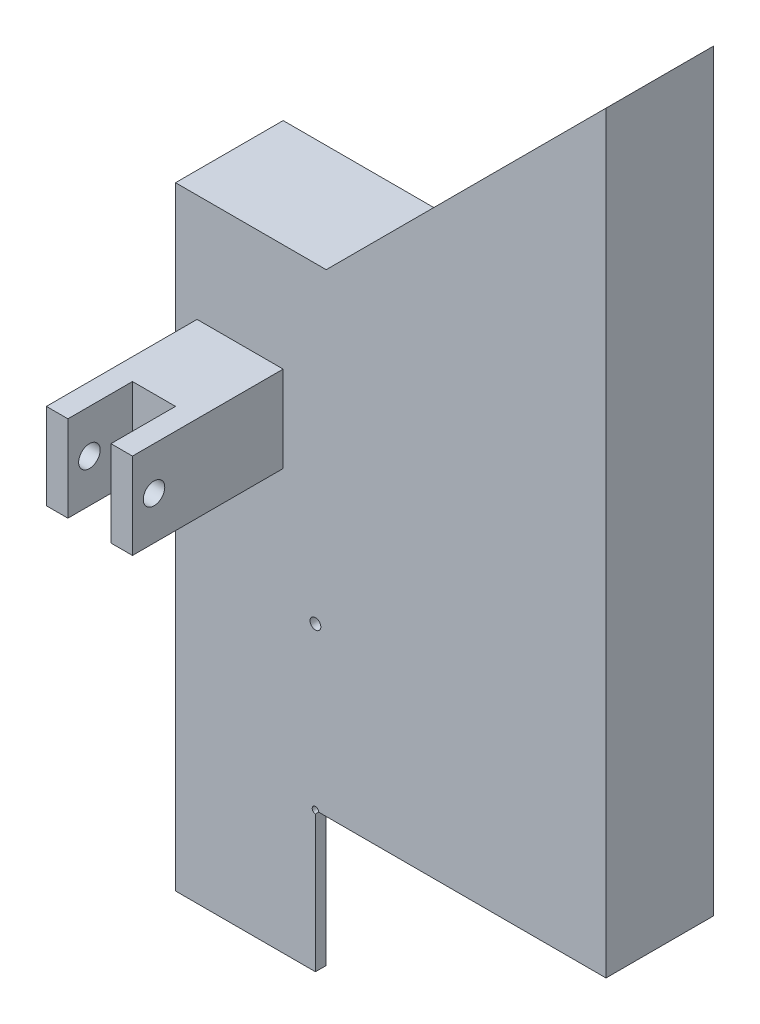
SolidWorks part; units mm, degrees
ref_plane "Přední rovina" through (0, 0, 0) normal (0, 0, 1) x (1, 0, 0)
ref_plane "Horní rovina" through (0, 0, 0) normal (0, 1, 0) x (1, 0, 0)
ref_plane "Pravá rovina" through (0, 0, 0) normal (1, 0, 0) x (0, 0, -1)
sketch "Skica1" plane through (0, 0, 0) normal (0, 0, 1) x (1, 0, 0)
  line L0 (0, 0) -> (200, 0)
  line L1 (200, 0) -> (200, 350)
  line L2 (200, 350) -> (70, 220)
  line L3 (70, 220) -> (0, 220)
  line L4 (0, 220) -> (0, 0)
  dimension "D1" = 350
  dimension "D2" = 200
  dimension "D3" = 70
  dimension "D4" = 220
extrude "Přidat vysunutím1" add sketch "Skica1" along normal blind 50
sketch "Skica2" plane through (0, 0, 0) normal (0, -1, 0) x (1, 0, 0)
  line L1 (0, 50) -> (130, 50)
  line L2 (0, 50) -> (0, 45)
  line L3 (0, 45) -> (130, 45)
  line L4 (130, 50) -> (130, 45)
  dimension "D1" = 130
  dimension "D2" = 5
extrude "Přidat vysunutím2" add sketch "Skica2" along normal blind 65
sketch "Skica3" plane through (0, 0, 50) normal (0, 0, 1) x (1, 0, 0)
  line L1 (130, -65) -> (65, -65)
  line L2 (130, -65) -> (130, 0)
  line L3 (130, 0) -> (65, 0)
  line L4 (65, -65) -> (65, 0)
  dimension "D1" = 65
  dimension "D2" = 65
extrude "Odebrat vysunutím1" cut sketch "Skica3" against normal blind 5
sketch "Skica4" plane through (0, 0, 50) normal (0, 0, 1) x (1, 0, 0)
  line L0 (70, 220) -> (0, 220) construction
  line L1 (10, 170) -> (50, 170)
  line L2 (10, 170) -> (10, 130)
  line L3 (10, 130) -> (50, 130)
  line L4 (50, 170) -> (50, 130)
  line L5 (0, 220) -> (0, -65) construction
  dimension "D1" = 40
  dimension "D2" = 40
  dimension "D3" = 50
  dimension "D4" = 10
extrude "Přidat vysunutím3" add sketch "Skica4" along normal blind 40
sketch "Skica5" plane through (0, 0, 90) normal (0, 0, 1) x (1, 0, 0)
  line L0 (10, 130) -> (50, 130) construction
  line L1 (10, 170) -> (20, 170)
  line L2 (10, 170) -> (10, 130)
  line L3 (10, 130) -> (20, 130)
  line L4 (20, 170) -> (20, 130)
  line L6 (50, 170) -> (40, 170)
  line L7 (50, 170) -> (50, 130)
  line L8 (50, 130) -> (40, 130)
  line L9 (40, 170) -> (40, 130)
  dimension "D1" = 10
  dimension "D2" = 10
extrude "Přidat vysunutím4" add sketch "Skica5" along normal blind 30
sketch "Skica6" plane through (50, 0, 0) normal (1, 0, 0) x (0, 0, -1)
  line L0 (-120, 130) -> (-50, 130) construction
  line L1 (-120, 130) -> (-120, 170) construction
  circle A0 centre (-110, 150) radius 5
  dimension "D1" = 10
  dimension "D2" = 20
  dimension "D3" = 10
extrude "Odebrat vysunutím2" cut sketch "Skica6" against normal blind 40
sketch "Skica7" plane through (0, 0, 50) normal (0, 0, 1) x (1, 0, 0)
  line L0 (65, -65) -> (0, -65) construction
  line L1 (0, 220) -> (0, -65) construction
  circle A0 centre (65, 75) radius 2.5
  dimension "D1" = 5
  dimension "D2" = 140
  dimension "D3" = 65
extrude "Odebrat vysunutím3" cut sketch "Skica7" against normal blind 55
sketch "Skica8" plane through (0, 0, 50) normal (0, 0, 1) x (1, 0, 0)
  line L0 (0, 220) -> (0, -65) construction
  line L1 (65, -65) -> (0, -65) construction
  circle A0 centre (65, 0) radius 1.5
  dimension "D1" = 3
  dimension "D2" = 65
  dimension "D3" = 65
extrude "Odebrat vysunutím4" cut sketch "Skica8" against normal blind 50
